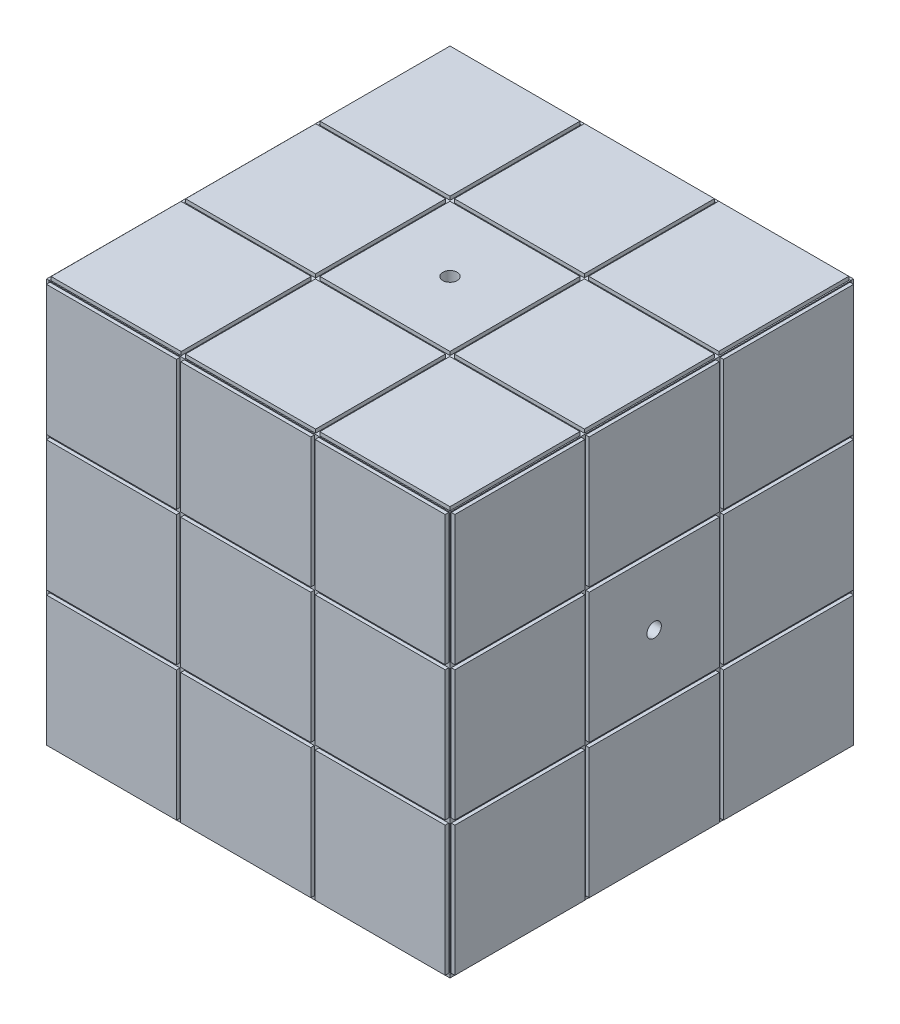
SolidWorks part; units mm, degrees
ref_plane "前视基准面" through (0, 0, 0) normal (0, 0, 1) x (1, 0, 0)
ref_plane "上视基准面" through (0, 0, 0) normal (0, 1, 0) x (1, 0, 0)
ref_plane "右视基准面" through (0, 0, 0) normal (1, 0, 0) x (0, 0, -1)
sketch "草图1" plane through (0, 0, 0) normal (0, 0, 1) x (1, 0, 0)
  line L1 (-28.25, 28.25) -> (28.25, 28.25)
  line L2 (-28.25, 28.25) -> (-28.25, -28.25)
  line L3 (-28.25, -28.25) -> (28.25, -28.25)
  line L4 (28.25, 28.25) -> (28.25, -28.25)
  line L5 (-28.25, 28.25) -> (28.25, -28.25) construction
  line L6 (-28.25, -28.25) -> (28.25, 28.25) construction
  point P0 (0, 0)
  dimension "D1" = 56.5
  dimension "D2" = 56.5
extrude "凸台-拉伸1" add sketch "草图1" along normal blind 56.5
sketch "草图2" plane through (0, 0, 56.5) normal (0, 0, 1) x (1, 0, 0)
  line L0 (-28.25, 0) -> (28.25, 0) construction
  line L1 (-27.625, 27.62) -> (-9.625, 27.62)
  line L2 (-27.625, 27.62) -> (-27.625, 9.62)
  line L3 (-27.625, 9.62) -> (-9.625, 9.62)
  line L4 (-9.625, 27.62) -> (-9.625, 9.62)
  line L5 (-27.625, 27.62) -> (-9.625, 9.62) construction
  line L6 (-27.625, 9.62) -> (-9.625, 27.62) construction
  line L7 (-28.25, 28.25) -> (-28.25, -28.25) construction
  line L8 (28.25, -28.25) -> (28.25, 28.25) construction
  line L9 (28.25, 28.25) -> (-28.25, 28.25) construction
  line L10 (-27.625, -27.62) -> (-9.625, -27.62)
  line L11 (-27.625, -27.62) -> (-27.625, -9.62)
  line L12 (-27.625, -9.62) -> (-9.625, -9.62)
  line L13 (-9.625, -27.62) -> (-9.625, -9.62)
  line L14 (8.975, 27.62) -> (8.975, 9.62)
  line L15 (-9.625, -9) -> (-27.625, -9)
  line L16 (-9.625, -9) -> (-9.625, 9)
  line L17 (-9.625, 9) -> (-27.625, 9)
  line L18 (-27.625, -9) -> (-27.625, 9)
  line L19 (-9.625, -9) -> (-27.625, 9) construction
  line L20 (-9.625, 9) -> (-27.625, -9) construction
  line L21 (-9.025, 27.62) -> (8.975, 27.62)
  line L22 (-9.025, 27.62) -> (-9.025, 9.62)
  line L23 (-9.025, 9.62) -> (8.975, 9.62)
  line L24 (8.975, -9) -> (8.975, 9)
  line L25 (8.975, 9) -> (-9.025, 9)
  line L26 (-9.025, -9) -> (-9.025, 9)
  line L27 (8.975, -9) -> (-9.025, -9)
  line L28 (-9.025, -9.62) -> (8.975, -9.62)
  line L29 (8.975, -27.62) -> (8.975, -9.62)
  line L30 (-9.025, -27.62) -> (8.975, -27.62)
  line L31 (-9.025, -27.62) -> (-9.025, -9.62)
  line L32 (27.575, 27.62) -> (27.575, 9.62)
  line L33 (9.575, 27.62) -> (27.575, 27.62)
  line L34 (9.575, 27.62) -> (9.575, 9.62)
  line L35 (9.575, 9.62) -> (27.575, 9.62)
  line L36 (27.575, -9) -> (27.575, 9)
  line L37 (27.575, 9) -> (9.575, 9)
  line L38 (9.575, -9) -> (9.575, 9)
  line L39 (27.575, -9) -> (9.575, -9)
  line L40 (9.575, -9.62) -> (27.575, -9.62)
  line L41 (27.575, -27.62) -> (27.575, -9.62)
  line L42 (9.575, -27.62) -> (27.575, -27.62)
  line L43 (9.575, -27.62) -> (9.575, -9.62)
  point P0 (-18.625, 18.62)
  point P18 (-18.625, 0)
  dimension "D1" = 18
  dimension "D2" = 18
  dimension "D3" = 0.625
  dimension "D4" = 0.63
  dimension "D5" = 18
  dimension "D6" = 18
  dimension "D7" = 0.625
  dimension "D8" = 3
extrude "切除-拉伸1" cut sketch "草图2" against normal blind 0.5 flip side to cut
sketch "草图3" plane through (0, 0, 0) normal (0, 0, -1) x (-1, 0, 0)
  line L4 (-28.25, 28.25) -> (-28.25, -28.25)
  line L5 (28.25, 28.25) -> (-28.25, 28.25)
  line L6 (28.25, -28.25) -> (28.25, 28.25)
  line L7 (-28.25, -28.25) -> (28.25, -28.25)
  line L8 (-28.25, 28.25) -> (-28.25, -28.25)
  line L9 (28.25, 28.25) -> (-28.25, 28.25)
  line L10 (28.25, -28.25) -> (28.25, 28.25)
  line L11 (-28.25, -28.25) -> (28.25, -28.25)
  line L12 (27.625, 27.62) -> (27.625, 9.62) construction
  line L13 (27.625, 9.62) -> (9.625, 9.62) construction
  line L14 (-9.575, 9.62) -> (-27.575, 9.62) construction
  line L15 (-27.575, 9.62) -> (-27.575, 27.62) construction
  line L16 (-27.575, 27.62) -> (-9.575, 27.62) construction
  line L17 (-9.575, 27.62) -> (-9.575, 9.62) construction
  line L18 (-8.975, 9.62) -> (-8.975, 27.62) construction
  line L19 (9.025, 27.62) -> (9.025, 9.62) construction
  line L20 (-8.975, 27.62) -> (9.025, 27.62) construction
  line L21 (9.625, 9.62) -> (9.625, 27.62) construction
  line L22 (9.625, 27.62) -> (27.625, 27.62) construction
  line L23 (27.625, 27.62) -> (27.625, 9.62)
  line L24 (27.625, 9.62) -> (9.625, 9.62)
  line L25 (-9.575, 9.62) -> (-27.575, 9.62)
  line L26 (-27.575, 9.62) -> (-27.575, 27.62)
  line L27 (-27.575, 27.62) -> (-9.575, 27.62)
  line L28 (-9.575, 27.62) -> (-9.575, 9.62)
  line L29 (-8.975, 9.62) -> (-8.975, 27.62)
  line L30 (9.025, 27.62) -> (9.025, 9.62)
  line L31 (-8.975, 27.62) -> (9.025, 27.62)
  line L32 (9.625, 9.62) -> (9.625, 27.62)
  line L33 (9.625, 27.62) -> (27.625, 27.62)
  line L34 (-27.575, -9.62) -> (-9.575, -9.62) construction
  line L35 (-9.575, -9.62) -> (-9.575, -27.62) construction
  line L36 (-9.575, -27.62) -> (-27.575, -27.62) construction
  line L37 (-27.575, -27.62) -> (-27.575, -9.62) construction
  line L38 (-8.975, -9.62) -> (9.025, -9.62) construction
  line L39 (9.025, -9.62) -> (9.025, -27.62) construction
  line L40 (9.025, -27.62) -> (-8.975, -27.62) construction
  line L41 (-8.975, -27.62) -> (-8.975, -9.62) construction
  line L42 (9.625, -9.62) -> (27.625, -9.62) construction
  line L43 (27.625, -9.62) -> (27.625, -27.62) construction
  line L44 (27.625, -27.62) -> (9.625, -27.62) construction
  line L45 (9.625, -27.62) -> (9.625, -9.62) construction
  line L46 (-27.575, 9) -> (-9.575, 9) construction
  line L47 (-9.575, 9) -> (-9.575, -9) construction
  line L48 (-9.575, -9) -> (-27.575, -9) construction
  line L49 (-27.575, -9) -> (-27.575, 9) construction
  line L50 (-8.975, 9) -> (9.025, 9) construction
  line L51 (9.025, 9) -> (9.025, -9) construction
  line L52 (9.025, -9) -> (-8.975, -9) construction
  line L53 (-8.975, -9) -> (-8.975, 9) construction
  line L54 (9.625, 9) -> (27.625, 9) construction
  line L55 (27.625, 9) -> (27.625, -9) construction
  line L56 (27.625, -9) -> (9.625, -9) construction
  line L57 (9.625, -9) -> (9.625, 9) construction
  line L58 (-27.575, -9.62) -> (-9.575, -9.62)
  line L59 (-9.575, -9.62) -> (-9.575, -27.62)
  line L60 (-9.575, -27.62) -> (-27.575, -27.62)
  line L61 (-27.575, -27.62) -> (-27.575, -9.62)
  line L62 (-8.975, -9.62) -> (9.025, -9.62)
  line L63 (9.025, -9.62) -> (9.025, -27.62)
  line L64 (9.025, -27.62) -> (-8.975, -27.62)
  line L65 (-8.975, -27.62) -> (-8.975, -9.62)
  line L66 (9.625, -9.62) -> (27.625, -9.62)
  line L67 (27.625, -9.62) -> (27.625, -27.62)
  line L68 (27.625, -27.62) -> (9.625, -27.62)
  line L69 (9.625, -27.62) -> (9.625, -9.62)
  line L70 (-27.575, 9) -> (-9.575, 9)
  line L71 (-9.575, 9) -> (-9.575, -9)
  line L72 (-9.575, -9) -> (-27.575, -9)
  line L73 (-27.575, -9) -> (-27.575, 9)
  line L74 (-8.975, 9) -> (9.025, 9)
  line L75 (9.025, 9) -> (9.025, -9)
  line L76 (9.025, -9) -> (-8.975, -9)
  line L77 (-8.975, -9) -> (-8.975, 9)
  line L78 (9.625, 9) -> (27.625, 9)
  line L79 (27.625, 9) -> (27.625, -9)
  line L80 (27.625, -9) -> (9.625, -9)
  line L81 (9.625, -9) -> (9.625, 9)
  line L82 (-8.975, 9.62) -> (9.025, 9.62)
  dimension "D1" = 0
extrude "切除-拉伸2" cut sketch "草图3" against normal blind 0.5
sketch "草图4" plane through (-28.25, 0, 0) normal (-1, 0, 0) x (0, 0, 1)
  line L2 (0.63, 27.62) -> (18.63, 27.62)
  line L3 (0.63, 27.62) -> (0.63, 9.62)
  line L4 (0.63, 9.62) -> (18.63, 9.62)
  line L5 (18.63, 27.62) -> (18.63, 9.62)
  line L6 (0.63, 27.62) -> (18.63, 9.62) construction
  line L7 (0.63, 9.62) -> (18.63, 27.62) construction
  line L9 (0, 9.62) -> (0, 27.62) construction
  line L10 (56, 28.25) -> (0.5, 28.25) construction
  line L11 (0, 0) -> (56.5, 0) construction
  line L12 (56.5, 9) -> (56.5, -9) construction
  line L13 (0.63, -9.62) -> (18.63, -27.62) construction
  line L14 (0.63, -27.62) -> (18.63, -9.62) construction
  line L15 (18.63, -27.62) -> (18.63, -9.62)
  line L16 (0.63, -9.62) -> (18.63, -9.62)
  line L17 (0.63, -27.62) -> (0.63, -9.62)
  line L18 (0.63, -27.62) -> (18.63, -27.62)
  line L19 (9.63, 18.62) -> (9.63, -5.6907) construction
  line L20 (18.63, -9) -> (0.63, -9)
  line L21 (18.63, -9) -> (18.63, 9)
  line L22 (18.63, 9) -> (0.63, 9)
  line L23 (0.63, -9) -> (0.63, 9)
  line L24 (18.63, -9) -> (0.63, 9) construction
  line L25 (18.63, 9) -> (0.63, -9) construction
  line L26 (19.23, 27.62) -> (37.23, 27.62)
  line L27 (37.23, 27.62) -> (37.23, 9.62)
  line L28 (19.23, 9.62) -> (37.23, 9.62)
  line L29 (19.23, 27.62) -> (19.23, 9.62)
  line L30 (37.23, -9) -> (19.23, -9)
  line L31 (19.23, -9) -> (19.23, 9)
  line L32 (37.23, 9) -> (19.23, 9)
  line L33 (37.23, -9) -> (37.23, 9)
  line L34 (37.23, -27.62) -> (37.23, -9.62)
  line L35 (19.23, -9.62) -> (37.23, -9.62)
  line L36 (19.23, -27.62) -> (37.23, -27.62)
  line L37 (19.23, -27.62) -> (19.23, -9.62)
  line L38 (37.83, 27.62) -> (55.83, 27.62)
  line L39 (55.83, 27.62) -> (55.83, 9.62)
  line L40 (37.83, 9.62) -> (55.83, 9.62)
  line L41 (37.83, 27.62) -> (37.83, 9.62)
  line L42 (55.83, -9) -> (37.83, -9)
  line L43 (37.83, -9) -> (37.83, 9)
  line L44 (55.83, 9) -> (37.83, 9)
  line L45 (55.83, -9) -> (55.83, 9)
  line L46 (55.83, -27.62) -> (55.83, -9.62)
  line L47 (37.83, -9.62) -> (55.83, -9.62)
  line L48 (37.83, -27.62) -> (55.83, -27.62)
  line L49 (37.83, -27.62) -> (37.83, -9.62)
  point P0 (9.63, 18.62)
  point P19 (9.63, -18.62)
  point P20 (9.63, 0)
  dimension "D1" = 18
  dimension "D2" = 18
  dimension "D3" = 0.63
  dimension "D4" = 0.63
  dimension "D5" = 18
  dimension "D6" = 18
  dimension "D7" = 3
extrude "切除-拉伸3" cut sketch "草图4" against normal blind 0.5 flip side to cut
sketch "草图5" plane through (28.25, 0, 0) normal (1, 0, 0) x (0, 0, -1)
  line L0 (-37.83, -9.62) -> (-37.83, -27.62) construction
  line L1 (-37.83, -27.62) -> (-55.83, -27.62) construction
  line L2 (-55.83, -27.62) -> (-55.83, -9.62) construction
  line L3 (-55.83, -9.62) -> (-37.83, -9.62) construction
  line L4 (-18.63, 27.62) -> (-18.63, 9.62)
  line L5 (-0.63, 27.62) -> (-18.63, 27.62)
  line L6 (-0.63, 9.62) -> (-0.63, 27.62)
  line L7 (-18.63, 9.62) -> (-0.63, 9.62)
  line L8 (-18.63, 27.62) -> (-18.63, 9.62)
  line L9 (-0.63, 27.62) -> (-18.63, 27.62)
  line L10 (-0.63, 9.62) -> (-0.63, 27.62)
  line L11 (-18.63, 9.62) -> (-0.63, 9.62)
  line L12 (-19.23, -9.62) -> (-19.23, -27.62) construction
  line L13 (-19.23, -27.62) -> (-37.23, -27.62) construction
  line L14 (-37.23, -27.62) -> (-37.23, -9.62) construction
  line L15 (-37.23, -9.62) -> (-19.23, -9.62) construction
  line L16 (-0.63, -9.62) -> (-0.63, -27.62) construction
  line L17 (-0.63, -27.62) -> (-18.63, -27.62) construction
  line L18 (-18.63, -27.62) -> (-18.63, -9.62) construction
  line L19 (-18.63, -9.62) -> (-0.63, -9.62) construction
  line L20 (-55.83, 9) -> (-37.83, 9) construction
  line L21 (-37.83, 9) -> (-37.83, -9) construction
  line L22 (-37.83, -9) -> (-55.83, -9) construction
  line L23 (-55.83, -9) -> (-55.83, 9) construction
  line L24 (-37.23, 9) -> (-19.23, 9) construction
  line L25 (-19.23, 9) -> (-19.23, -9) construction
  line L26 (-19.23, -9) -> (-37.23, -9) construction
  line L27 (-37.23, -9) -> (-37.23, 9) construction
  line L28 (-0.63, 9) -> (-0.63, -9) construction
  line L29 (-0.63, -9) -> (-18.63, -9) construction
  line L30 (-18.63, -9) -> (-18.63, 9) construction
  line L31 (-18.63, 9) -> (-0.63, 9) construction
  line L32 (-37.83, 9.62) -> (-55.83, 9.62) construction
  line L33 (-55.83, 9.62) -> (-55.83, 27.62) construction
  line L34 (-55.83, 27.62) -> (-37.83, 27.62) construction
  line L35 (-37.83, 27.62) -> (-37.83, 9.62) construction
  line L36 (-19.23, 9.62) -> (-37.23, 9.62) construction
  line L37 (-37.23, 9.62) -> (-37.23, 27.62) construction
  line L38 (-37.23, 27.62) -> (-19.23, 27.62) construction
  line L39 (-19.23, 27.62) -> (-19.23, 9.62) construction
  line L40 (-37.83, -9.62) -> (-37.83, -27.62)
  line L41 (-37.83, -27.62) -> (-55.83, -27.62)
  line L42 (-55.83, -27.62) -> (-55.83, -9.62)
  line L43 (-55.83, -9.62) -> (-37.83, -9.62)
  line L44 (-19.23, -9.62) -> (-19.23, -27.62)
  line L45 (-19.23, -27.62) -> (-37.23, -27.62)
  line L46 (-37.23, -27.62) -> (-37.23, -9.62)
  line L47 (-37.23, -9.62) -> (-19.23, -9.62)
  line L48 (-0.63, -9.62) -> (-0.63, -27.62)
  line L49 (-0.63, -27.62) -> (-18.63, -27.62)
  line L50 (-18.63, -27.62) -> (-18.63, -9.62)
  line L51 (-18.63, -9.62) -> (-0.63, -9.62)
  line L52 (-55.83, 9) -> (-37.83, 9)
  line L53 (-37.83, 9) -> (-37.83, -9)
  line L54 (-37.83, -9) -> (-55.83, -9)
  line L55 (-55.83, -9) -> (-55.83, 9)
  line L56 (-37.23, 9) -> (-19.23, 9)
  line L57 (-19.23, 9) -> (-19.23, -9)
  line L58 (-19.23, -9) -> (-37.23, -9)
  line L59 (-37.23, -9) -> (-37.23, 9)
  line L60 (-0.63, 9) -> (-0.63, -9)
  line L61 (-0.63, -9) -> (-18.63, -9)
  line L62 (-18.63, -9) -> (-18.63, 9)
  line L63 (-18.63, 9) -> (-0.63, 9)
  line L64 (-37.83, 9.62) -> (-55.83, 9.62)
  line L65 (-55.83, 9.62) -> (-55.83, 27.62)
  line L66 (-55.83, 27.62) -> (-37.83, 27.62)
  line L67 (-37.83, 27.62) -> (-37.83, 9.62)
  line L68 (-19.23, 9.62) -> (-37.23, 9.62)
  line L69 (-37.23, 9.62) -> (-37.23, 27.62)
  line L70 (-37.23, 27.62) -> (-19.23, 27.62)
  line L71 (-19.23, 27.62) -> (-19.23, 9.62)
  dimension "D1" = 0
extrude "切除-拉伸4" cut sketch "草图5" against normal blind 0.5 flip side to cut
sketch "草图6" plane through (0, 28.25, 0) normal (0, 1, 0) x (1, 0, 0)
  line L0 (-27.625, 0) -> (-9.625, 0) construction
  line L1 (-9.62, -18.63) -> (-27.62, -18.63)
  line L2 (-9.62, -18.63) -> (-9.62, -0.63)
  line L3 (-9.62, -0.63) -> (-27.62, -0.63)
  line L4 (-27.62, -18.63) -> (-27.62, -0.63)
  line L5 (-9.62, -18.63) -> (-27.62, -0.63) construction
  line L6 (-9.62, -0.63) -> (-27.62, -18.63) construction
  line L7 (-28.25, -18.63) -> (-28.25, -0.63) construction
  line L8 (-27.75, -28.25) -> (28.25, -28.23) construction
  line L9 (-27.75, -56) -> (-27.75, -0.5) construction
  line L10 (28.25, -19.23) -> (28.25, -37.23) construction
  line L11 (-9.6003, -55.857) -> (-27.6131, -37.8699) construction
  line L12 (-9.6131, -37.857) -> (-27.6003, -55.8699) construction
  line L13 (-27.6131, -37.8699) -> (-27.6003, -55.8699)
  line L14 (-9.6003, -55.857) -> (-27.6003, -55.8699)
  line L15 (-9.6131, -37.857) -> (-9.6003, -55.857)
  line L16 (-9.6131, -37.857) -> (-27.6131, -37.8699)
  line L17 (-18.62, -0.63) -> (-18.6003, -55.8635) construction
  line L18 (8.98, -0.63) -> (-9.02, -0.63)
  line L19 (-9.6101, -37.2467) -> (-27.6101, -37.2467)
  line L20 (-9.6101, -37.2467) -> (-9.6101, -19.2467)
  line L21 (-9.6101, -19.2467) -> (-27.6101, -19.2467)
  line L22 (-27.6101, -37.2467) -> (-27.6101, -19.2467)
  line L23 (-9.6101, -37.2467) -> (-27.6101, -19.2467) construction
  line L24 (-9.6101, -19.2467) -> (-27.6101, -37.2467) construction
  line L25 (8.98, -18.63) -> (8.98, -0.63)
  line L26 (-9.02, -18.63) -> (-9.02, -0.63)
  line L27 (8.9899, -19.2467) -> (-9.0101, -19.2467)
  line L28 (8.98, -18.63) -> (-9.02, -18.63)
  line L29 (8.9899, -37.2467) -> (8.9899, -19.2467)
  line L30 (8.9899, -37.2467) -> (-9.0101, -37.2467)
  line L31 (-9.0101, -37.2467) -> (-9.0101, -19.2467)
  line L32 (8.9869, -37.857) -> (-9.0131, -37.8699)
  line L33 (8.9869, -37.857) -> (8.9997, -55.857)
  line L34 (8.9997, -55.857) -> (-9.0003, -55.8699)
  line L35 (-9.0131, -37.8699) -> (-9.0003, -55.8699)
  line L36 (27.58, -0.63) -> (9.58, -0.63)
  line L37 (27.58, -18.63) -> (27.58, -0.63)
  line L38 (9.58, -18.63) -> (9.58, -0.63)
  line L39 (27.5899, -19.2467) -> (9.5899, -19.2467)
  line L40 (27.58, -18.63) -> (9.58, -18.63)
  line L41 (27.5899, -37.2467) -> (27.5899, -19.2467)
  line L42 (27.5899, -37.2467) -> (9.5899, -37.2467)
  line L43 (9.5899, -37.2467) -> (9.5899, -19.2467)
  line L44 (27.5869, -37.857) -> (9.5869, -37.8699)
  line L45 (27.5869, -37.857) -> (27.5997, -55.857)
  line L46 (27.5997, -55.857) -> (9.5997, -55.8699)
  line L47 (9.5869, -37.8699) -> (9.5997, -55.8699)
  point P0 (-18.62, -9.63)
  point P19 (-18.6067, -46.8635)
  point P22 (-18.6101, -28.2467)
  dimension "D1" = 18
  dimension "D2" = 0.63
  dimension "D3" = 0.63
  dimension "D4" = 18
  dimension "D5" = 18
  dimension "D6" = 3
extrude "切除-拉伸5" cut sketch "草图6" against normal blind 0.5 flip side to cut
sketch "草图7" plane through (0, -28.25, 0) normal (0, -1, 0) x (1, 0, 0)
  line L0 (9.5997, 55.8699) -> (27.5997, 55.857) construction
  line L1 (27.5997, 55.857) -> (27.5869, 37.857) construction
  line L2 (27.5869, 37.857) -> (9.5869, 37.8699) construction
  line L3 (9.5869, 37.8699) -> (9.5997, 55.8699) construction
  line L4 (27.75, 0.5) -> (27.75, 56)
  line L5 (27.75, 56) -> (-27.75, 56)
  line L6 (-27.75, 56) -> (-27.75, 0.5)
  line L7 (-27.75, 0.5) -> (27.75, 0.5)
  line L8 (27.75, 0.5) -> (27.75, 56)
  line L9 (27.75, 56) -> (-27.75, 56)
  line L10 (-27.75, 56) -> (-27.75, 0.5)
  line L11 (-27.75, 0.5) -> (27.75, 0.5)
  line L12 (-27.62, 18.63) -> (-27.62, 0.63)
  line L13 (-9.62, 18.63) -> (-27.62, 18.63)
  line L14 (-9.62, 0.63) -> (-9.62, 18.63)
  line L15 (-27.62, 0.63) -> (-9.62, 0.63)
  line L16 (-27.62, 18.63) -> (-27.62, 0.63)
  line L17 (-9.62, 18.63) -> (-27.62, 18.63)
  line L18 (-9.62, 0.63) -> (-9.62, 18.63)
  line L19 (-27.62, 0.63) -> (-9.62, 0.63)
  line L20 (-9.0003, 55.8699) -> (8.9997, 55.857) construction
  line L21 (8.9997, 55.857) -> (8.9869, 37.857) construction
  line L22 (8.9869, 37.857) -> (-9.0131, 37.8699) construction
  line L23 (-9.0131, 37.8699) -> (-9.0003, 55.8699) construction
  line L24 (-9.6003, 55.857) -> (-9.6131, 37.857) construction
  line L25 (-9.6131, 37.857) -> (-27.6131, 37.8699) construction
  line L26 (-27.6131, 37.8699) -> (-27.6003, 55.8699) construction
  line L27 (-27.6003, 55.8699) -> (-9.6003, 55.857) construction
  line L28 (9.5899, 19.2467) -> (9.5899, 37.2467) construction
  line L29 (9.5899, 37.2467) -> (27.5899, 37.2467) construction
  line L30 (27.5899, 37.2467) -> (27.5899, 19.2467) construction
  line L31 (27.5899, 19.2467) -> (9.5899, 19.2467) construction
  line L32 (-9.0101, 19.2467) -> (-9.0101, 37.2467) construction
  line L33 (-9.0101, 37.2467) -> (8.9899, 37.2467) construction
  line L34 (8.9899, 37.2467) -> (8.9899, 19.2467) construction
  line L35 (8.9899, 19.2467) -> (-9.0101, 19.2467) construction
  line L36 (-27.6101, 19.2467) -> (-27.6101, 37.2467) construction
  line L37 (-27.6101, 37.2467) -> (-9.6101, 37.2467) construction
  line L38 (-9.6101, 37.2467) -> (-9.6101, 19.2467) construction
  line L39 (-9.6101, 19.2467) -> (-27.6101, 19.2467) construction
  line L40 (9.58, 0.63) -> (9.58, 18.63) construction
  line L41 (9.58, 18.63) -> (27.58, 18.63) construction
  line L42 (27.58, 18.63) -> (27.58, 0.63) construction
  line L43 (27.58, 0.63) -> (9.58, 0.63) construction
  line L44 (-9.02, 0.63) -> (-9.02, 18.63) construction
  line L45 (-9.02, 18.63) -> (8.98, 18.63) construction
  line L46 (8.98, 18.63) -> (8.98, 0.63) construction
  line L47 (8.98, 0.63) -> (-9.02, 0.63) construction
  line L48 (9.5997, 55.8699) -> (27.5997, 55.857)
  line L49 (27.5997, 55.857) -> (27.5869, 37.857)
  line L50 (27.5869, 37.857) -> (9.5869, 37.8699)
  line L51 (9.5869, 37.8699) -> (9.5997, 55.8699)
  line L52 (-9.0003, 55.8699) -> (8.9997, 55.857)
  line L53 (8.9997, 55.857) -> (8.9869, 37.857)
  line L54 (8.9869, 37.857) -> (-9.0131, 37.8699)
  line L55 (-9.0131, 37.8699) -> (-9.0003, 55.8699)
  line L56 (-9.6003, 55.857) -> (-9.6131, 37.857)
  line L57 (-9.6131, 37.857) -> (-27.6131, 37.8699)
  line L58 (-27.6131, 37.8699) -> (-27.6003, 55.8699)
  line L59 (-27.6003, 55.8699) -> (-9.6003, 55.857)
  line L60 (9.5899, 19.2467) -> (9.5899, 37.2467)
  line L61 (9.5899, 37.2467) -> (27.5899, 37.2467)
  line L62 (27.5899, 37.2467) -> (27.5899, 19.2467)
  line L63 (27.5899, 19.2467) -> (9.5899, 19.2467)
  line L64 (-9.0101, 19.2467) -> (-9.0101, 37.2467)
  line L65 (-9.0101, 37.2467) -> (8.9899, 37.2467)
  line L66 (8.9899, 37.2467) -> (8.9899, 19.2467)
  line L67 (8.9899, 19.2467) -> (-9.0101, 19.2467)
  line L68 (-27.6101, 19.2467) -> (-27.6101, 37.2467)
  line L69 (-27.6101, 37.2467) -> (-9.6101, 37.2467)
  line L70 (-9.6101, 37.2467) -> (-9.6101, 19.2467)
  line L71 (-9.6101, 19.2467) -> (-27.6101, 19.2467)
  line L72 (9.58, 0.63) -> (9.58, 18.63)
  line L73 (9.58, 18.63) -> (27.58, 18.63)
  line L74 (27.58, 18.63) -> (27.58, 0.63)
  line L75 (27.58, 0.63) -> (9.58, 0.63)
  line L76 (-9.02, 0.63) -> (-9.02, 18.63)
  line L77 (-9.02, 18.63) -> (8.98, 18.63)
  line L78 (8.98, 18.63) -> (8.98, 0.63)
  line L79 (8.98, 0.63) -> (-9.02, 0.63)
  dimension "D1" = 0
  dimension "D2" = 0
extrude "切除-拉伸6" cut sketch "草图7" against normal blind 0.5
sketch "草图8" plane through (28.25, 0, 0) normal (1, 0, 0) x (0, 0, -1)
  line L0 (0, 9) -> (0, -9) construction
  line L2 (-37.2467, 28.25) -> (-19.2467, 28.25) construction
  circle A0 centre (-28.25, 0) radius 1
  point P6 (-28.2467, 28.25)
  dimension "D1" = 28.25
  dimension "D2" = 28.25
  dimension "D3" = 2
extrude "切除-拉伸7" cut sketch "草图8" against normal blind 10
sketch "草图9" plane through (0, 0, 0) normal (0, 0, -1) x (-1, 0, 0)
  circle A0 centre (0, 0) radius 1
  dimension "D1" = 2
extrude "切除-拉伸8" cut sketch "草图9" against normal blind 10
sketch "草图10" plane through (0, 28.25, 0) normal (0, 1, 0) x (1, 0, 0)
  line L0 (-9.025, 0) -> (8.975, 0) construction
  line L1 (28.25, -19.23) -> (28.25, -37.23) construction
  circle A0 centre (0, -28.25) radius 1
  dimension "D1" = 28.25
  dimension "D2" = 2
  dimension "D3" = 28.25
extrude "切除-拉伸9" cut sketch "草图10" against normal blind 10
